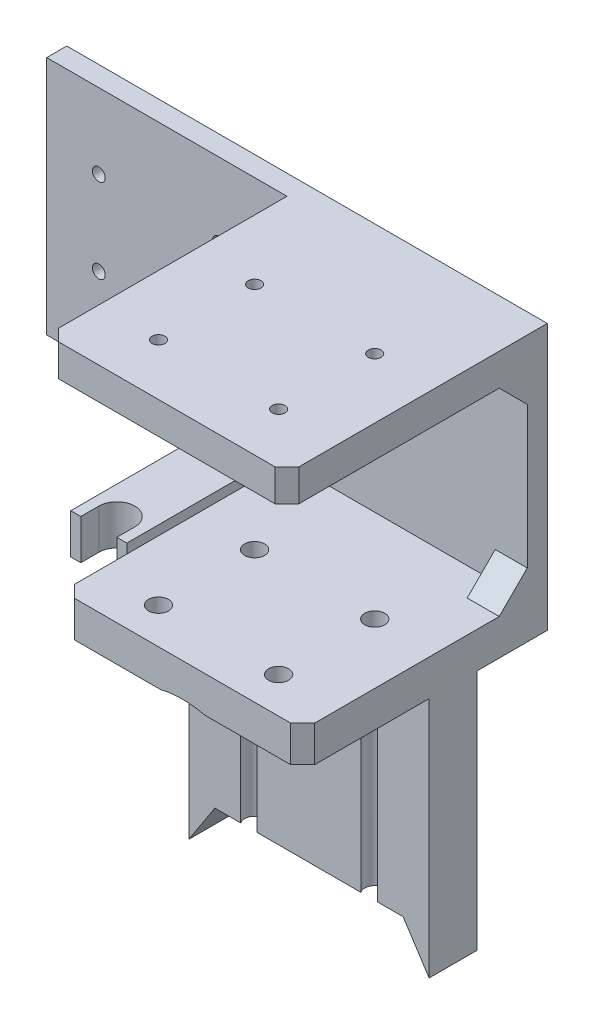
SolidWorks part; units mm, degrees
ref_plane "前视基准面" through (0, 0, 0) normal (0, 0, 1) x (1, 0, 0)
ref_plane "上视基准面" through (0, 0, 0) normal (0, 1, 0) x (1, 0, 0)
ref_plane "右视基准面" through (0, 0, 0) normal (1, 0, 0) x (0, 0, -1)
other "Configuration Table"
sketch "草图1" plane through (0, 0, 0) normal (0, 0, 1) x (1, 0, 0)
  line L0 (-25, 75) -> (-25, 25) construction
  line L2 (35, 20) -> (-85, 20)
  line L3 (35, 20) -> (35, 80)
  line L4 (35, 80) -> (-85, 80)
  line L5 (-85, 20) -> (-85, 80)
  line L6 (35, 20) -> (-85, 80) construction
  line L7 (35, 80) -> (-85, 20) construction
  point P4 (-25, 50)
  dimension "D1" = 60
  dimension "D2" = 120
extrude "凸台-拉伸1" add sketch "草图1" along normal blind 5
sketch "草图2" plane through (0, 0, 0) normal (0, 0, -1) x (-1, 0, 0)
  circle A0 centre (-25, 75) radius 1.75
  circle A1 centre (25, 75) radius 1.75
  circle A2 centre (75, 75) radius 1.75
  circle A3 centre (75, 25) radius 1.75
  circle A4 centre (25, 25) radius 1.75
  circle A5 centre (-25, 25) radius 1.75
  dimension "D1" = 3.5
  dimension "D2" = 3.5
  dimension "D3" = 3.5
  dimension "D4" = 3.5
  dimension "D5" = 3.5
  dimension "D6" = 3.5
sketch "草图3" plane through (0, 0, 5) normal (0, 0, 1) x (1, 0, 0)
  line L0 (-25, 80) -> (-25, 20) construction
  line L1 (35, 80) -> (-85, 80) construction
  line L2 (-85, 20) -> (35, 20) construction
  line L3 (35, 20) -> (35, 80) construction
  line L8 (-25, 80) -> (35, 80)
  line L9 (-25, 80) -> (-25, 72)
  line L10 (-25, 72) -> (35, 72)
  line L11 (35, 80) -> (35, 72)
  point P6 (-25, 50)
  dimension "D1" = 8
extrude "凸台-拉伸3" add sketch "草图3" along normal blind 60
sketch "草图4" plane through (35, 0, 0) normal (1, 0, 0) x (0, 0, -1)
  line L11 (0, -145) -> (0, 145) construction
  line L12 (0, 13.617) -> (-61.0881, 13.617)
  line L13 (0, 13.617) -> (0, 22.617)
  line L14 (0, 22.617) -> (-61.0881, 22.617)
  line L15 (-61.0881, 13.617) -> (-61.0881, 22.617)
  dimension "D1" = 9
extrude "凸台-拉伸4" add sketch "草图4" against normal blind 60
sketch "草图6" plane through (0, 0, 0) normal (0, 0, -1) x (-1, 0, 0)
  line L0 (-5, 13.617) -> (-5, 34.4671) construction
  line L1 (25, 13.617) -> (-35, 13.617) construction
  line L2 (-5, 13.617) -> (-5, -49.7308) construction
  circle A0 centre (-5, -9.2139) radius 23.5
  dimension "D1" = 47
extrude "切除-拉伸1" cut sketch "草图6" against normal through all
sketch "草图7" plane through (0, 0, 0) normal (0, 0, -1) x (-1, 0, 0)
  line L1 (-35, 13.617) -> (25, 13.617)
  line L2 (-35, 13.617) -> (-35, -36.8103)
  line L4 (25, 13.617) -> (25, -36.8103)
  line L5 (-42.9383, -36.8103) -> (32.9383, -36.8103) construction
  line L8 (25, -36.8103) -> (25, -46.8103)
  line L9 (25, -46.8103) -> (18.816, -37.2964)
  line L10 (-35, -36.8103) -> (-35, -46.8103)
  line L11 (-35, -46.8103) -> (-28.816, -37.2964)
  arc A0 (18.4934, -36.2537) -> (-28.4934, -36.2537) centre (-5, -36.8103) ccw
  arc A1 (18.816, -37.2964) -> (18.4934, -36.2537) centre (20.4928, -36.2064) cw
  arc A2 (-28.816, -37.2964) -> (-28.4934, -36.2537) centre (-30.4928, -36.2064) ccw
  point P12 (-5, -36.8103)
  point P17 (18.5, -36.8103)
  point P20 (-28.5, -36.8103)
  line M14 (-35, 13.617) -> (-10.5677, 13.617)
  line M16 (0.5677, 13.617) -> (25, 13.617)
  dimension "D3" = 2
  dimension "D1" = 10
  dimension "D2" = 10
extrude "凸台-拉伸5" add sketch "草图7" against normal blind 50 contours L2 L5 A2 A0 M14 | A1 L5 L4 A0 M16 | L5 A1 L9 L8 | L5 L10 L11 A2
sketch "草图8" plane through (35, 0, 0) normal (1, 0, 0) x (0, 0, -1)
  line L0 (-50, 13.617) -> (-29.5, 13.617)
  line L1 (0, -46.8103) -> (0, 80) construction
  line L2 (-50, -46.8103) -> (0, -46.8103) construction
  line L4 (-29.5, -46.8103) -> (-29.5, 13.617)
  line L5 (-29.5, 13.617) -> (-17.5, 13.617)
  line L6 (-17.5, -46.8103) -> (-17.5, 13.617)
  line L7 (-31, -44.2893) -> (-31, -71.2893) construction
  line L9 (-17.5, -46.8103) -> (0, -46.8103)
  line L10 (0, -46.8103) -> (0, 13.617)
  line L11 (-50, 13.617) -> (-50, -46.8103)
  line L12 (-50, -46.8103) -> (-29.5, -46.8103)
  line L13 (-17.5, 13.617) -> (0, 13.617)
  line M9 (-50, 13.617) -> (-50, -46.8103)
  line M10 (-50, -46.8103) -> (0, -46.8103)
  line M11 (0, -46.8103) -> (0, 80)
  dimension "D1" = 12
  dimension "D2" = 1.5
extrude "切除-拉伸2" cut sketch "草图8" against normal blind 60 contours L4 L0 M10 M9 | L13 L6 M10 M11
sketch "草图9" plane through (0, 20, 0) normal (0, -1, 0) x (1, 0, 0)
  line L0 (-85, 0) -> (-25, 0) construction
  line L3 (-32.5, 0) -> (-41.5, 0)
  line L6 (-41.5, 0) -> (-44, 0)
  line L7 (-41.5, 35.5) -> (-41.5, 40)
  line L8 (-41.5, 40) -> (-44, 40)
  line L9 (-44, 0) -> (-44, 40)
  line L10 (-32.5, 0) -> (-30, 0)
  line L11 (-32.5, 35.5) -> (-32.5, 40)
  line L12 (-32.5, 40) -> (-30, 40)
  line L13 (-30, 0) -> (-30, 40)
  arc A0 (-41.5, 35.5) -> (-32.5, 35.5) centre (-37, 35.5) ccw
  dimension "D1" = 9
  dimension "D2" = 2.5
  dimension "D3" = 40
  dimension "D4" = 2.5
  dimension "D5" = 40
extrude "凸台-拉伸6" add sketch "草图9" along normal blind 10
sketch "草图11" plane through (0, 72, 0) normal (0, -1, 0) x (-1, 0, 0)
  circle A0 centre (-20, -52.0881) radius 1.6
  circle A1 centre (10, -28.0881) radius 1.6
  circle A2 centre (-20, -28.0881) radius 1.6
  circle A3 centre (10, -52.0881) radius 1.6
  point P3 (10, -52.0881)
  point P4 (10, -28.0881)
  point P5 (-20, -28.0881)
extrude "切除-拉伸3" cut sketch "草图11" against normal through all
sketch "草图12" plane through (0, 0, 0) normal (0, 0, -1) x (-1, 0, 0)
  line L0 (42, 67.85) -> (42, 62.85) construction
  line L1 (42, 33.65) -> (42, 38.65) construction
  line L2 (72, 33.65) -> (72, 38.65) construction
  circle A0 centre (42, 40.25) radius 1.6
  circle A1 centre (42, 61.25) radius 1.6
  arc A2 (44.1, 65.75) -> (39.9, 65.75) centre (42, 65.75) ccw construction
  arc A3 (39.9, 35.75) -> (44.1, 35.75) centre (42, 35.75) ccw construction
  circle A4 centre (72, 40.25) radius 1.6
  circle A5 centre (72, 61.25) radius 1.6
  arc A7 (69.9, 35.75) -> (74.1, 35.75) centre (72, 35.75) ccw construction
  dimension "D1" = 3.2
  dimension "D2" = 3.2
  dimension "D3" = 5
  dimension "D5" = 3.2
  dimension "D6" = 3.2
  dimension "D7" = 5
  dimension "D4" = 5
extrude "切除-拉伸4" cut sketch "草图12" against normal through all
sketch "草图13" plane through (35, 0, 0) normal (1, 0, 0) x (0, 0, -1)
  line L0 (-5, 65) -> (-12, 72)
  line L1 (-5, 22.617) -> (-5, 72) construction
  line L2 (-65, 72) -> (-5, 72) construction
  dimension "D1" = 7
  dimension "D2" = 7
rib "筋1" sketch "草图13" sketch "草图13" thickness 8 extrusion direction parallel to sketch draft on no parameters "D1"=8
ref_plane "基准面1" through (5, 0, 0) normal (1, 0, 0) x (0, 0, -1)
mirror "镜向1" about plane through (5, 0, 0) normal (1, 0, 0) of "筋1"
ref_plane "基准面2" through (0, 47.3085, 0) normal (0, -1, 0) x (-1, 0, 0)
mirror "镜向2" about plane through (0, 47.3085, 0) normal (0, -1, 0) of "镜向1", "筋1"
sketch "草图15" plane through (0, 0, 0) normal (0, 0, -1) x (-1, 0, 0)
  line L0 (44, 10) -> (44, 20) construction
  line L1 (25, 13.617) -> (30, 13.617)
  line L2 (25, 13.617) -> (25, 20)
  line L3 (25, 20) -> (30, 20)
  line L4 (30, 13.617) -> (30, 20)
  line L5 (44, 13.617) -> (49, 13.617)
  line L6 (44, 13.617) -> (44, 20)
  line L7 (44, 20) -> (49, 20)
  line L8 (49, 13.617) -> (49, 20)
  line L9 (85, 20) -> (44, 20) construction
  dimension "D1" = 5
extrude "凸台-拉伸7" add sketch "草图15" against normal blind 10
chamfer "倒角2" distance 2 angle 45 1 edges at (-49, 16.8085, 10)
chamfer "倒角3" distance 3 angle 45 4 edges at (35, 18.117, 61.0881) (-25, 18.117, 61.0881) (-25, 76, 65) (35, 76, 65)
sketch "草图16" plane through (0, 22.617, 0) normal (0, 1, 0) x (1, 0, 0)
  circle A0 centre (20, -52.0881) radius 2.5
  circle A1 centre (-10, -52.0881) radius 2.5
  circle A2 centre (-10, -28.0881) radius 2.5
  circle A3 centre (20, -28.0881) radius 2.5
  dimension "D1" = 5
  dimension "D2" = 5
  dimension "D3" = 5
  dimension "D4" = 5
extrude "切除-拉伸5" cut sketch "草图16" against normal through all
sketch "草图18" plane through (0, 0, 0) normal (0, 0, -1) x (-1, 0, 0)
  circle A0 centre (75, 75) radius 3.75
  circle A1 centre (25, 75) radius 3.75
  circle A2 centre (-25, 75) radius 3.75
  circle A3 centre (-25, 25) radius 3.75
  circle A4 centre (25, 25) radius 3.75
  circle A5 centre (75, 25) radius 3.75
  dimension "D1" = 7.5
  dimension "D2" = 7.5
  dimension "D3" = 7.5
  dimension "D4" = 7.5
  dimension "D5" = 7.5
  dimension "D6" = 7.5
extrude "切除-拉伸7" cut sketch "草图18" against normal blind 2
